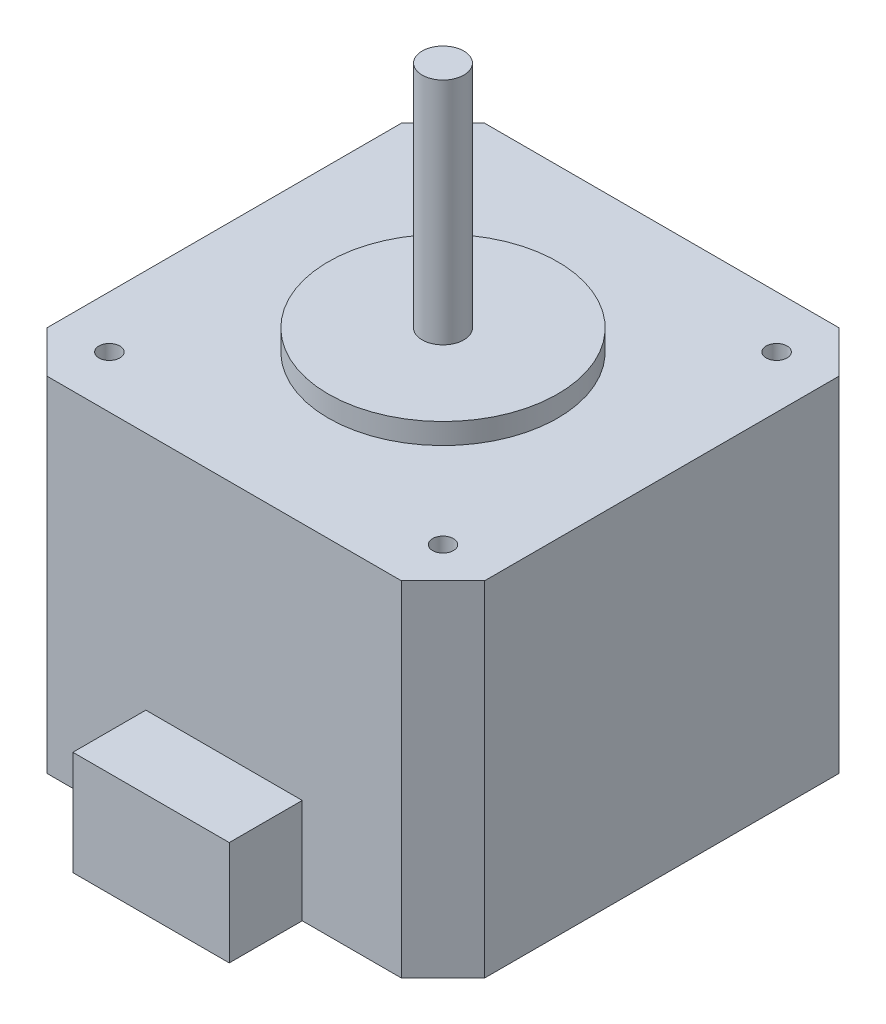
SolidWorks part; units mm, degrees
ref_plane "Front Plane" through (0, 0, 0) normal (0, 0, 1) x (1, 0, 0)
ref_plane "Top Plane" through (0, 0, 0) normal (0, 1, 0) x (1, 0, 0)
ref_plane "Right Plane" through (0, 0, 0) normal (1, 0, 0) x (0, 0, -1)
sketch "Sketch1" plane through (0, 0, 0) normal (0, 1, 0) x (1, 0, 0)
  line L1 (0, 0) -> (42, 0)
  line L2 (0, 0) -> (0, -42)
  line L3 (0, -42) -> (42, -42)
  line L4 (42, 0) -> (42, -42)
  dimension "D1" = 42
extrude "Boss-Extrude1" add sketch "Sketch1" along normal blind 33
sketch "Sketch2" plane through (0, 33, 0) normal (0, 1, 0) x (1, 0, 0)
  line L0 (42, 0) -> (0, 0) construction
  line L3 (42, -42) -> (42, 0) construction
  circle A0 centre (21, -21) radius 11
  dimension "D1" = 22
  dimension "D2" = 21
  dimension "D3" = 21
extrude "Boss-Extrude2" add sketch "Sketch2" along normal blind 2 contours A0
sketch "Sketch3" plane through (0, 35, 0) normal (0, 1, 0) x (1, 0, 0)
  circle A0 centre (21, -21) radius 2
  circle A1 centre (21, -21) radius 11 construction
  dimension "D1" = 4
extrude "Boss-Extrude3" add sketch "Sketch3" along normal blind 22
sketch "Sketch4" plane through (0, 0, 42) normal (0, 0, 1) x (1, 0, 0)
  line L0 (0, 0) -> (42, 0) construction
  line L1 (13.5, 0) -> (28.5, 0)
  line L2 (13.5, 0) -> (13.5, 10)
  line L3 (13.5, 10) -> (28.5, 10)
  line L4 (28.5, 0) -> (28.5, 10)
  line L5 (42, 33) -> (42, 0) construction
  dimension "D1" = 15
  dimension "D2" = 13.5
  dimension "D3" = 10
extrude "Boss-Extrude4" add sketch "Sketch4" along normal blind 7
sketch "Sketch5" plane through (0, 33, 0) normal (0, 1, 0) x (1, 0, 0)
  line L0 (42, -42) -> (42, 0) construction
  line L1 (37, -5) -> (5, -5)
  line L2 (37, -5) -> (37, -37)
  line L3 (37, -37) -> (5, -37)
  line L4 (5, -5) -> (5, -37)
  line L5 (42, 0) -> (0, 0) construction
  line L6 (0, -42) -> (42, -42) construction
  line L7 (0, 0) -> (0, -42) construction
  dimension "D1" = 5
  dimension "D2" = 5
  dimension "D3" = 5
  dimension "D4" = 5
hole_wizard "Ø2.0mm Clearance Dowel Hole1" positions "3DSketch1" profile "Sketch6" hole size "Ø2.0" standard "ANSI Metric"
sketch3d "3DSketch1"
  point P0 (37, 33, 5)
  point P3 (37, 33, 37)
  point P6 (5, 33, 37)
  point P9 (5, 33, 5)
sketch "Sketch6" plane through (37, 33, 5) normal (1, 0, 0) x (0, 0, 1)
  line L0 (0, 0) -> (0, 8.6009)
  line L1 (0, 8.6009) -> (1, 8)
  line L2 (1, 8) -> (1, 0)
  line L5 (1, 0) -> (0, 0)
  line L10 (0, 8.6009) -> (-1, 8) construction
  line L11 (0, -6.35) -> (0, 107.95) construction
  dimension "Hole Dia." = 2
  dimension "Hole Depth" = 8
  dimension "Drill Angle" = 118
chamfer "Chamfer1" distance 4 angle 45 4 edges at (42, 16.5, 42) (0, 16.5, 42) (0, 16.5, 0) (42, 16.5, 0)
